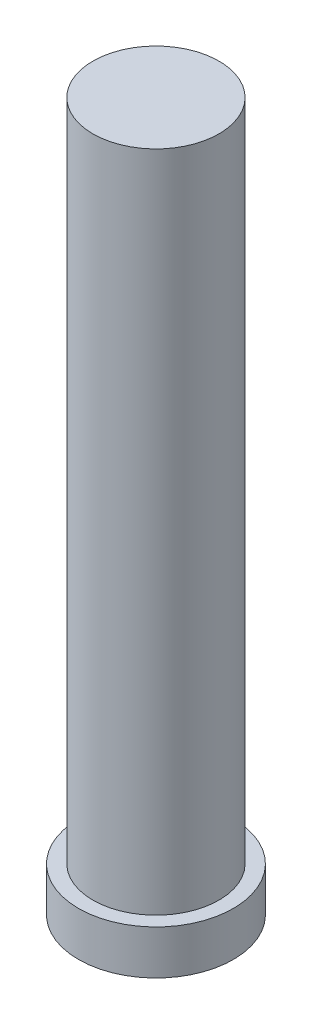
SolidWorks part; units mm, degrees
ref_plane "Front Plane" through (0, 0, 0) normal (0, 0, 1) x (1, 0, 0)
ref_plane "Top Plane" through (0, 0, 0) normal (0, 1, 0) x (1, 0, 0)
ref_plane "Right Plane" through (0, 0, 0) normal (1, 0, 0) x (0, 0, -1)
sketch "Sketch1" plane through (0, 0, 0) normal (0, 1, 0) x (1, 0, 0)
  circle A0 centre (0, 0) radius 3.5
extrude "Boss-Extrude1" add sketch "Sketch1" along normal blind 2
sketch "Sketch2" plane through (0, 2, 0) normal (0, 1, 0) x (1, 0, 0)
  circle A0 centre (0, 0) radius 2.85
extrude "Boss-Extrude2" add sketch "Sketch2" along normal blind 30
